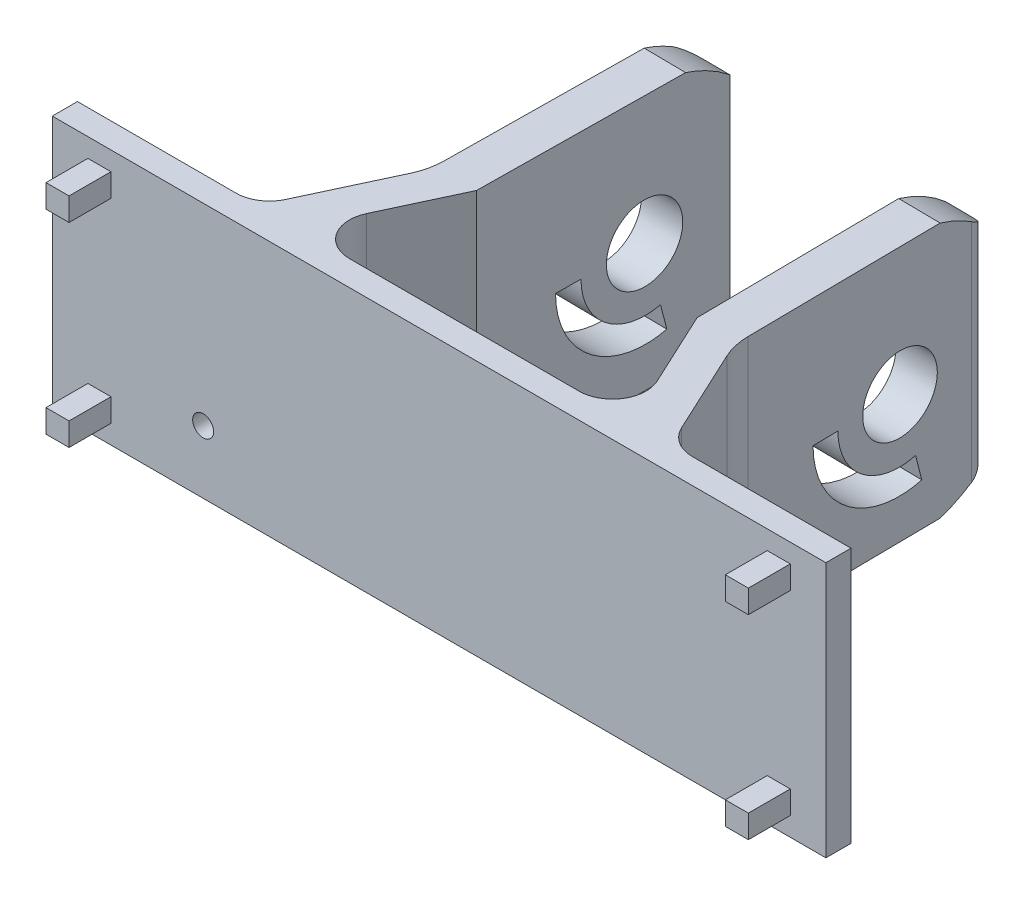
SolidWorks part; units mm, degrees
ref_plane "Front Plane" through (0, 0, 0) normal (0, 0, 1) x (1, 0, 0)
ref_plane "Top Plane" through (0, 0, 0) normal (0, 1, 0) x (1, 0, 0)
ref_plane "Right Plane" through (0, 0, 0) normal (1, 0, 0) x (0, 0, -1)
sketch "Sketch1" plane through (0, 0, 0) normal (0, 0, 1) x (1, 0, 0)
  line L8 (46.15, -14.65) -> (46.15, 15.85)
  line L9 (46.15, 15.85) -> (-46.15, 15.85)
  line L10 (-46.15, 15.85) -> (-46.15, -14.65)
  line L11 (-46.15, -14.65) -> (46.15, -14.65)
  line L12 (42.15, -12.65) -> (-42.15, -12.65)
  line L13 (42.15, 13.85) -> (42.15, -12.65)
  line L14 (-42.15, 13.85) -> (42.15, 13.85)
  line L15 (-42.15, 13.85) -> (-42.15, -12.65)
extrude "Boss-Extrude1" add sketch "Sketch1" along normal blind 3 contours L10 L11 L8 L9 L15 L14 L13 L12 | L14 L15 L12 L13
sketch "Sketch2" plane through (0, 0, 3) normal (0, 0, 1) x (1, 0, 0)
  line L0 (0, 0) -> (0, 30.6096) construction
  line L1 (-42.15, 13.85) -> (-39.15, 13.85)
  line L2 (-42.15, 13.85) -> (-42.15, 10.85)
  line L3 (-42.15, 10.85) -> (-39.15, 10.85)
  line L4 (-42.15, -12.65) -> (42.15, -12.65)
  line L5 (-42.15, 13.85) -> (-42.15, -12.65)
  line L6 (42.15, 13.85) -> (-42.15, 13.85)
  line L7 (42.15, -12.65) -> (42.15, 13.85)
  line L8 (-42.15, -12.65) -> (42.15, -12.65) construction
  line L9 (-42.15, 13.85) -> (-42.15, -12.65) construction
  line L10 (42.15, 13.85) -> (-42.15, 13.85) construction
  line L11 (42.15, -12.65) -> (42.15, 13.85) construction
  line L12 (-39.15, 13.85) -> (-39.15, 10.85)
  line L13 (0, 0) -> (10.9733, 0) construction
  line L14 (42.15, 10.85) -> (39.15, 10.85)
  line L15 (39.15, 13.85) -> (39.15, 10.85)
  line L20 (42.15, 13.85) -> (39.15, 13.85)
  line L21 (42.15, 13.85) -> (42.15, 10.85)
  line L23 (42.15, -12.65) -> (39.15, -12.65)
  line L24 (42.15, -12.65) -> (42.15, -9.65)
  line L25 (42.15, -9.65) -> (39.15, -9.65)
  line L26 (39.15, -12.65) -> (39.15, -9.65)
  line L27 (-42.15, -12.65) -> (-39.15, -12.65)
  line L28 (-42.15, -12.65) -> (-42.15, -9.65)
  line L29 (-42.15, -9.65) -> (-39.15, -9.65)
  line L30 (-39.15, -12.65) -> (-39.15, -9.65)
  dimension "D2" = 3
  dimension "D3" = 3
  dimension "D4" = 3
  dimension "D5" = 3
  dimension "D1" = 0
extrude "Boss-Extrude2" add sketch "Sketch2" along normal blind 5
sketch "Sketch13" plane through (0, 0, 8) normal (0, 0, 1) x (1, 0, 0)
  line L0 (-42.15, 13.85) -> (42.15, 13.85) construction
  line L1 (42.15, 13.85) -> (42.15, -12.65) construction
  line L2 (42.15, -12.65) -> (-42.15, -12.65) construction
  line L3 (-42.15, -12.65) -> (-42.15, 13.85) construction
  line L4 (-41.9, -12.4) -> (-41.9, 13.6)
  line L5 (-41.9, 13.6) -> (41.9, 13.6)
  line L6 (41.9, 13.6) -> (41.9, -12.4)
  line L7 (41.9, -12.4) -> (-41.9, -12.4)
  line L12 (-46.15, 15.85) -> (-46.15, -14.65)
  line L13 (-46.15, -14.65) -> (46.15, -14.65)
  line L14 (46.15, -14.65) -> (46.15, 15.85)
  line L15 (46.15, 15.85) -> (-46.15, 15.85)
  line L16 (-46.15, 15.85) -> (-46.15, -14.65)
  line L17 (-46.15, -14.65) -> (46.15, -14.65)
  line L18 (46.15, -14.65) -> (46.15, 15.85)
  line L19 (46.15, 15.85) -> (-46.15, 15.85)
  dimension "D1" = 0.25
  dimension "D2" = 0
extrude "Cut-Extrude9" cut sketch "Sketch13" against normal up to surface (5 mm away) up to face at (0, 0.6, 3)
sketch "Sketch12" plane through (0, 0, 3) normal (0, 0, 1) x (1, 0, 0)
  line L0 (-46.15, -14.65) -> (46.15, -14.65) construction
  line L1 (-46.15, 15.85) -> (-46.15, -14.65) construction
  circle A0 centre (-28.15, -7.15) radius 1.25
  dimension "D1" = 2.5
  dimension "D2" = 7.5
  dimension "D3" = 18
extrude "Cut-Extrude8" cut sketch "Sketch12" against normal blind 12
sketch "Sketch14" plane through (0, 15.85, 0) normal (0, 1, 0) x (1, 0, 0)
  line L0 (12.7998, 44.6306) -> (13.1514, 14.6326)
  line L1 (13.1514, 14.6326) -> (19.9747, 0)
  line L2 (17.8231, 42.6709) -> (18.1389, 15.7243)
  line L5 (-13.1514, 14.6326) -> (-12.7988, 44.4871)
  line L11 (0, 0) -> (0, 16.8352) construction
  line L12 (-12.7988, 44.4871) -> (-15.834, 44.4701)
  line L15 (15.8121, 44.6474) -> (12.7998, 44.6306)
  line L16 (24.6874, 0) -> (19.9747, 0)
  line L17 (-13.1514, 14.6326) -> (-19.9747, 0)
  line L18 (18.8879, 12.4371) -> (24.6874, 0)
  line L19 (-19.9747, 0) -> (-24.6874, 0)
  line L20 (46.15, 0) -> (-46.15, 0) construction
  line L21 (18.1591, 14) -> (18.1591, 7.5242) construction
  line L22 (-18.8877, 12.4375) -> (-24.6874, 0)
  line L24 (-17.8227, 42.4937) -> (-18.1388, 15.724)
  arc A0 (-18.8877, 12.4375) -> (-18.1388, 15.724) centre (-26.1382, 15.8184) ccw
  arc A1 (18.1389, 15.7243) -> (18.8879, 12.4371) centre (26.1384, 15.8181) ccw
  arc A2 (-17.8227, 42.4937) -> (-15.834, 44.4701) centre (-15.8228, 42.4701) cw
  arc A3 (17.8231, 42.6709) -> (15.8121, 44.6474) centre (15.8233, 42.6475) ccw
  point P22 (-18.1591, 14)
  dimension "D3" = 8
  dimension "D4" = 2
  dimension "D2" = 25
extrude "Boss-Extrude4" add sketch "Sketch14" against normal up to surface (30.5 mm away) up to face at (0, -14.65, 1.5)
fillet "Fillet1" radius 4 4 edges at (-19.9747, 0.6, 0) (19.9747, 0.6, 0) (-24.6874, 0.6, 0) (24.6874, 0.6, 0)
sketch "Sketch15" plane through (-18.3219, 0, -0.2163) normal (-0.9999, 0, -0.0118) x (-0.0118, 0, 0.9999)
  line L0 (-39.1212, 15.85) -> (-29.4388, 15.85) construction
  line L4 (-42.2803, -14.65) -> (-29.4388, -14.65) construction
  line L5 (-38.78, 0.6) -> (-34.28, 0.6) construction
  line L6 (-44.28, 0.6) -> (-44.28, 5.3641) construction
  line L8 (-39.1212, 15.85) -> (-39.1212, 17.87)
  line L9 (-39.1212, 17.87) -> (-55.9674, 17.87)
  line L10 (-55.9674, 17.87) -> (-55.9674, -17.8208)
  line L11 (-55.9674, -17.8208) -> (-39.1212, -17.8208)
  line L12 (-39.1212, -17.8208) -> (-39.1212, -14.65)
  line L13 (-36.156, -6.6616) -> (-36.9064, -9.5662)
  line L14 (-26.78, 0.6) -> (-23.78, 0.6)
  circle A0 centre (-34.28, 0.6) radius 4.5
  arc A3 (-39.1212, 15.85) -> (-39.1212, -14.65) centre (-34.28, 0.6) ccw
  arc A4 (-36.156, -6.6616) -> (-26.78, 0.6) centre (-34.28, 0.6) ccw
  arc A5 (-36.9064, -9.5662) -> (-23.78, 0.6) centre (-34.28, 0.6) ccw
  dimension "D1" = 9
  dimension "D3" = 15
  dimension "D4" = 3
  dimension "D5" = 32
  dimension "D2" = 10
extrude "Cut-Extrude10" cut sketch "Sketch15" against normal blind 51
